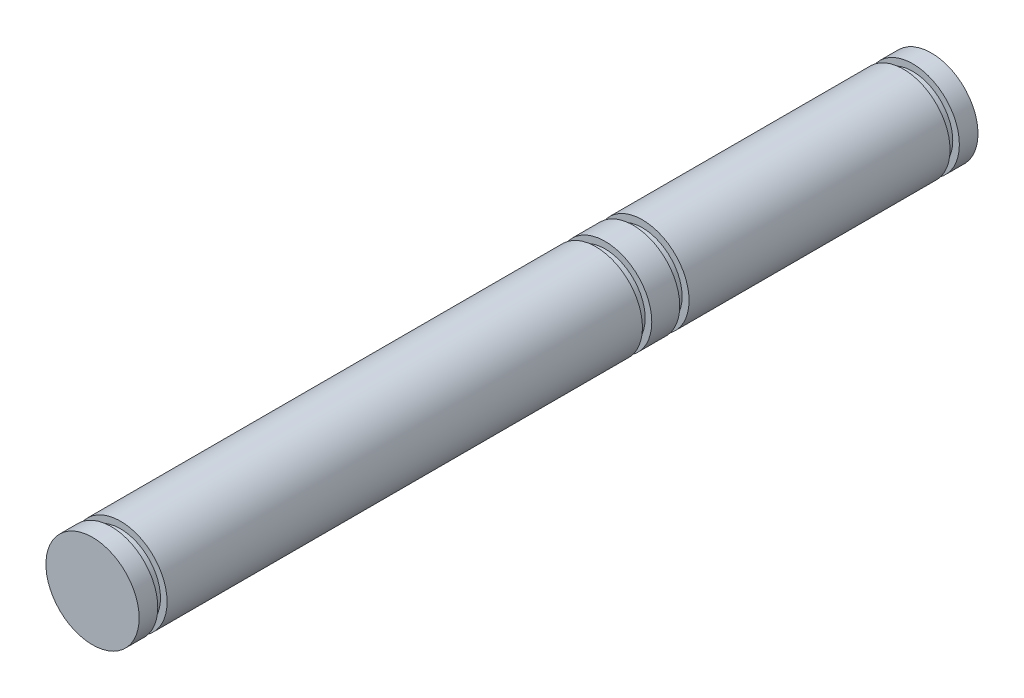
SolidWorks part; units mm, degrees
ref_plane "Vorne" through (0, 0, 0) normal (0, 0, 1) x (1, 0, 0)
ref_plane "Oben" through (0, 0, 0) normal (0, 1, 0) x (1, 0, 0)
ref_plane "Rechts" through (0, 0, 0) normal (1, 0, 0) x (0, 0, -1)
ref_plane "E_Boden" through (0, 1, 0) normal (0, 1, 0) x (1, 0, 0)
sketch "Skizze1" plane through (0, 0, 0) normal (1, 0, 0) x (0, 0, -1)
  line L0 (-17.9236, 0) -> (92.5153, 0) construction
  line L1 (-7.3158, 0) -> (-7.3158, 5)
  line L2 (-7.3158, 5) -> (-5.3158, 5)
  line L3 (-5.3158, 5) -> (-5.3158, 4.292)
  line L4 (-5.3158, 4.292) -> (-4.3158, 4.292)
  line L5 (-4.3158, 4.292) -> (-4.3158, 5)
  line L6 (-4.3158, 5) -> (46.6842, 5)
  line L7 (46.6842, 5) -> (46.6842, 4.292)
  line L8 (46.6842, 4.292) -> (47.6842, 4.292)
  line L9 (47.6842, 4.292) -> (47.6842, 5)
  line L10 (47.6842, 5) -> (50.6842, 5)
  line L11 (50.6842, 5) -> (50.6842, 4.2559)
  line L12 (50.6842, 4.2559) -> (51.6842, 4.2559)
  line L13 (51.6842, 4.2559) -> (51.6842, 5)
  line L14 (51.6842, 5) -> (79.6842, 5)
  line L15 (79.6842, 5) -> (79.6842, 4.292)
  line L16 (79.6842, 4.292) -> (80.6842, 4.292)
  line L17 (80.6842, 4.292) -> (80.6842, 5)
  line L18 (80.6842, 5) -> (82.6842, 5)
  line L19 (82.6842, 5) -> (82.6842, 0)
  line L20 (-7.3158, 0) -> (82.6842, 0)
  dimension "D1" = 5
  dimension "D2" = 2
  dimension "D3" = 1
  dimension "D4" = 51
  dimension "D5" = 1
  dimension "D6" = 3
  dimension "D7" = 1
  dimension "D8" = 28
  dimension "D9" = 1
  dimension "D10" = 2
  dimension "D11" = 5
  dimension "D12" = 5
  dimension "D13" = 5
revolve "Rotation1" add sketch "Skizze1" angle 360 about L20
